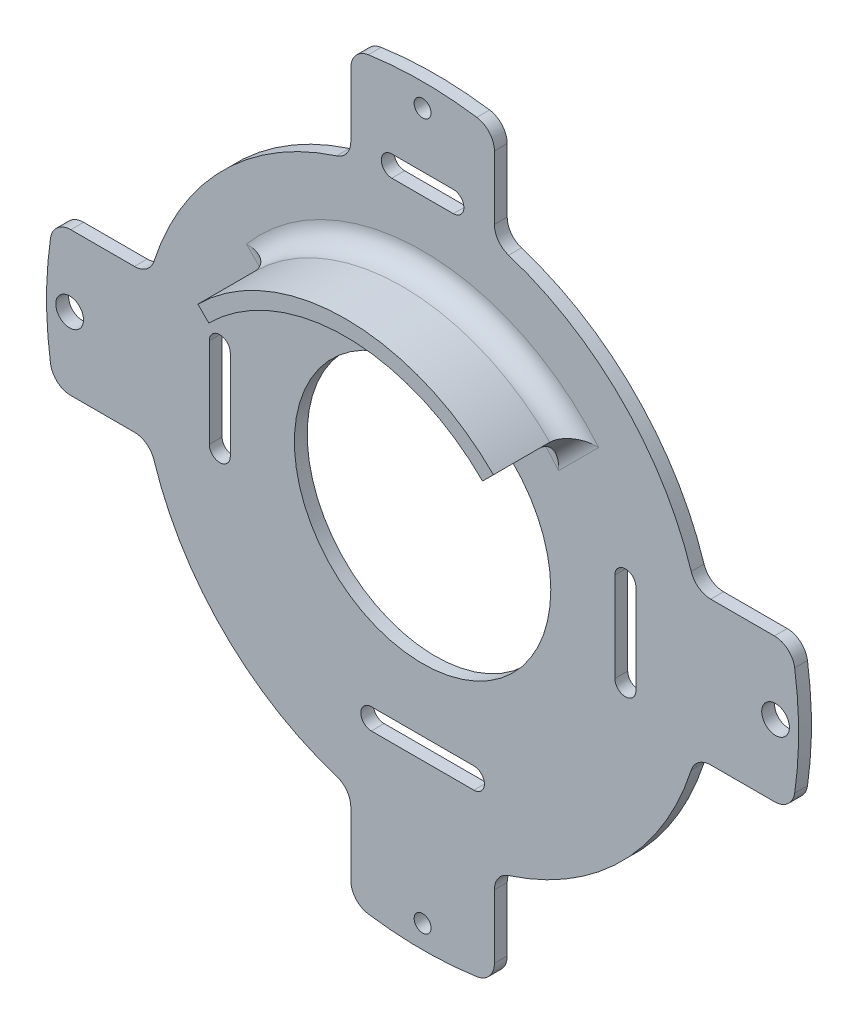
SolidWorks part; units mm, degrees
material "PETG"
ref_plane "Front Plane" through (0, 0, 0) normal (0, 0, 1) x (1, 0, 0)
ref_plane "Top Plane" through (0, 0, 0) normal (0, 1, 0) x (1, 0, 0)
ref_plane "Right Plane" through (0, 0, 0) normal (1, 0, 0) x (0, 0, -1)
sketch "Sketch1" plane through (0, 0, 0) normal (0, 0, 1) x (1, 0, 0)
  line L0 (0, 68.825) -> (0, -68.825) construction
  line L1 (-68.825, 0) -> (68.825, 0) construction
  line L2 (48.9898, -10) -> (64.049, -10) construction
  line L3 (10, -64.049) -> (10, -48.9898) construction
  line L4 (-10, -64.049) -> (-10, -48.9898) construction
  line L5 (-48.9898, -10) -> (-64.049, -10) construction
  line L77 (37.25, 0) -> (-37.25, 0) construction
  line L78 (-6, 56.05) -> (6, 56.05) construction
  line L79 (0, 37.25) -> (0, -37.25) construction
  line L80 (-41.6, 17.5) -> (-37.5, 17.5) construction
  line L81 (-37.5, 17.5) -> (-37.5, -17.5) construction
  line L82 (-37.5, -17.5) -> (-41.6, -17.5) construction
  line L83 (-41.6, -17.5) -> (-41.6, 17.5) construction
  line L84 (-37.5, 8.75) -> (-37.5, -8.75)
  line L85 (-41.6, -8.75) -> (-41.6, 8.75)
  line L98 (20, -37.25) -> (20, -41.35) construction
  line L99 (20, -41.35) -> (-20, -41.35) construction
  line L100 (-20, -41.35) -> (-20, -37.25) construction
  line L101 (-20, -37.25) -> (20, -37.25) construction
  line L102 (10, -41.35) -> (-10, -41.35)
  line L103 (-10, -37.25) -> (10, -37.25)
  line L110 (37.5, -17.5) -> (41.6, -17.5) construction
  line L111 (41.6, -17.5) -> (41.6, 17.5) construction
  line L112 (37.5, 17.5) -> (37.5, -17.5) construction
  line L113 (41.6, 17.5) -> (37.5, 17.5) construction
  line L114 (41.6, -8.75) -> (41.6, 8.75)
  line L115 (37.5, 8.75) -> (37.5, -8.75)
  line L116 (-6, 58.1) -> (6, 58.1)
  line L117 (-6, 54) -> (6, 54)
  circle A0 centre (0, 0) radius 76.2 construction
  circle A1 centre (0, 0) radius 68.825 construction
  circle A3 centre (0, 0) radius 64.825 construction
  circle A4 centre (0, 68.825) radius 1.65
  circle A7 centre (-68.825, 0) radius 2.7
  circle A10 centre (0, 0) radius 50 construction
  arc A13 (-64.049, -10) -> (-10, -64.049) centre (0, 0) ccw construction
  arc A14 (10, -64.049) -> (64.049, -10) centre (0, 0) ccw construction
  arc A18 (48.9898, -10) -> (10, -48.9898) centre (0, 0) cw construction
  arc A19 (-10, -48.9898) -> (-48.9898, -10) centre (0, 0) cw construction
  circle A48 centre (0, 0) radius 73.325
  circle A51 centre (0, 0) radius 44 construction
  circle A70 centre (0, 0) radius 37.25 construction
  circle A71 centre (0, 0) radius 25
  arc A72 (-37.5, -8.75) -> (-41.6, -8.75) centre (-39.55, -8.75) cw
  arc A73 (-41.6, 8.75) -> (-37.5, 8.75) centre (-39.55, 8.75) cw
  arc A78 (-10, -41.35) -> (-10, -37.25) centre (-10, -39.3) cw
  arc A79 (10, -37.25) -> (10, -41.35) centre (10, -39.3) cw
  arc A82 (37.5, -8.75) -> (41.6, -8.75) centre (39.55, -8.75) ccw
  arc A83 (41.6, 8.75) -> (37.5, 8.75) centre (39.55, 8.75) ccw
  arc A86 (-6, 58.1) -> (-6, 54) centre (-6, 56.05) ccw
  arc A87 (6, 54) -> (6, 58.1) centre (6, 56.05) ccw
  circle A92 centre (0, -68.825) radius 1.65
  circle A93 centre (68.825, 0) radius 2.7
  point P10 (0, 56.05)
  point P19 (0, 0)
  point P68 (64.049, 10)
  point P71 (48.9898, 10)
  point P74 (64.049, -10)
  point P77 (48.9898, -10)
  point P80 (10, -64.049)
  point P83 (10, -48.9898)
  point P86 (-10, -64.049)
  point P89 (-10, -48.9898)
  point P92 (-48.9898, -10)
  point P95 (-64.049, -10)
  point P131 (0, 0)
  point P132 (0, 0)
  point P165 (-37.5, 0)
  point P199 (0, -41.35)
  dimension "D1" = 152.4
  dimension "D2" = 137.65
  dimension "D5" = 3.3
  dimension "D7" = 0
  dimension "D8" = 4.1
  dimension "D9" = 100
  dimension "D10" = 10
  dimension "D20" = 88
  dimension "D12" = 4.1
  dimension "D22" = 74.5
  dimension "D23" = 50
  dimension "D24" = 0
  dimension "D6" = 5.4
  dimension "D11" = 10
  dimension "D13" = 12
  dimension "D14" = 54
  dimension "D15" = 4.5
  dimension "D28" = 4.1
  dimension "D29" = 35
  dimension "D30" = 17.5
  dimension "D33" = 37.5
  dimension "D38" = 40
  dimension "D39" = 20
  dimension "D40" = 37.25
  dimension "D4" = 4
extrude "Boss-Extrude1" add sketch "Sketch1" along normal blind 2.5
sketch "Sketch2" plane through (0, 0, 2.5) normal (0, 0, 1) x (1, 0, 0)
  line L0 (0, 0) -> (0, 68.825) construction
  line L1 (0, 0) -> (-26.6933, 26.6933) construction
  line L7 (-26.6933, 26.6933) -> (-28.8146, 28.8146)
  line L8 (26.6933, 26.6933) -> (28.8146, 28.8146)
  arc A1 (-26.6933, 26.6933) -> (26.6933, 26.6933) centre (0, 0) cw
  arc A3 (-28.8146, 28.8146) -> (28.8146, 28.8146) centre (0, 0) cw
  dimension "D1" = 45
  dimension "D2" = 37.75
  dimension "D3" = 3
extrude "Boss-Extrude2" add sketch "Sketch2" along normal blind 15
sketch "Sketch3" plane through (0, 0, 2.5) normal (0, 0, 1) x (1, 0, 0)
  line L0 (-31, 40.75) -> (31, 40.75) construction
  line L1 (-31, 43.75) -> (31, 43.75)
  line L2 (-31, 43.75) -> (-31, 46.25)
  line L3 (-31, 46.25) -> (31, 46.25)
  line L4 (31, 43.75) -> (31, 46.25)
  arc A0 (28.8146, 28.8146) -> (-28.8146, 28.8146) centre (0, 0) ccw construction
  point P4 (0, 46.25)
  dimension "D1" = 2.5
  dimension "D2" = 62
  dimension "D3" = 3
fillet "Fillet2" radius 4 4 edges at (-27.7539, 27.7539, 2.5) (27.7539, 27.7539, 2.5) (0, 37.75, 2.5) (0, 40.75, 2.5)
sketch "Sketch4" plane through (0, 0, 2.5) normal (0, 0, 1) x (1, 0, 0)
  line L2 (0, 68.825) -> (0, -68.825) construction
  line L7 (-68.825, 0) -> (68.825, 0) construction
  line L8 (71.9761, 14) -> (53.1883, 14)
  line L9 (-71.9761, -14) -> (-53.1883, -14)
  line L10 (-14, -53.1883) -> (-14, -71.9761)
  line L11 (-48.9898, -10) -> (-64.049, -10) construction
  line L12 (-10, -64.049) -> (-10, -48.9898) construction
  line L13 (71.9761, -14) -> (53.1883, -14)
  line L14 (14, -53.1883) -> (14, -71.9761)
  line L15 (14, 53.1883) -> (14, 71.9761)
  line L16 (-71.9761, 14) -> (-53.1883, 14)
  line L17 (-14, 53.1883) -> (-14, 71.9761)
  arc A0 (71.9761, 14) -> (14, 71.9761) centre (0, 0) ccw
  arc A6 (53.1883, 14) -> (14, 53.1883) centre (0, 0) ccw
  arc A7 (-53.1883, 14) -> (-14, 53.1883) centre (0, 0) cw
  circle A9 centre (0, 0) radius 73.325 construction
  arc A10 (-53.1883, -14) -> (-14, -53.1883) centre (0, 0) ccw
  arc A11 (-71.9761, -14) -> (-14, -71.9761) centre (0, 0) ccw
  circle A12 centre (0, 0) radius 50 construction
  arc A13 (53.1883, -14) -> (14, -53.1883) centre (0, 0) cw
  arc A14 (71.9761, -14) -> (14, -71.9761) centre (0, 0) cw
  arc A15 (-71.9761, 14) -> (-14, 71.9761) centre (0, 0) cw
  dimension "D3" = 5
  dimension "D1" = 4
  dimension "D2" = 4
extrude "Cut-Extrude1" cut sketch "Sketch4" against normal through all
fillet "Fillet1" radius 4 16 edges at (71.9761, -14, 1.25) (-71.9761, -14, 1.25) (-14, -71.9761, 1.25) (14, -71.9761, 1.25) (53.1883, -14, 1.25) (14, -53.1883, 1.25) (-53.1883, -14, 1.25) (-14, -53.1883, 1.25) (71.9761, 14, 1.25) (53.1883, 14, 1.25) (14, 53.1883, 1.25) (14, 71.9761, 1.25) (-14, 71.9761, 1.25) (-14, 53.1883, 1.25) (-53.1883, 14, 1.25) (-71.9761, 14, 1.25)
